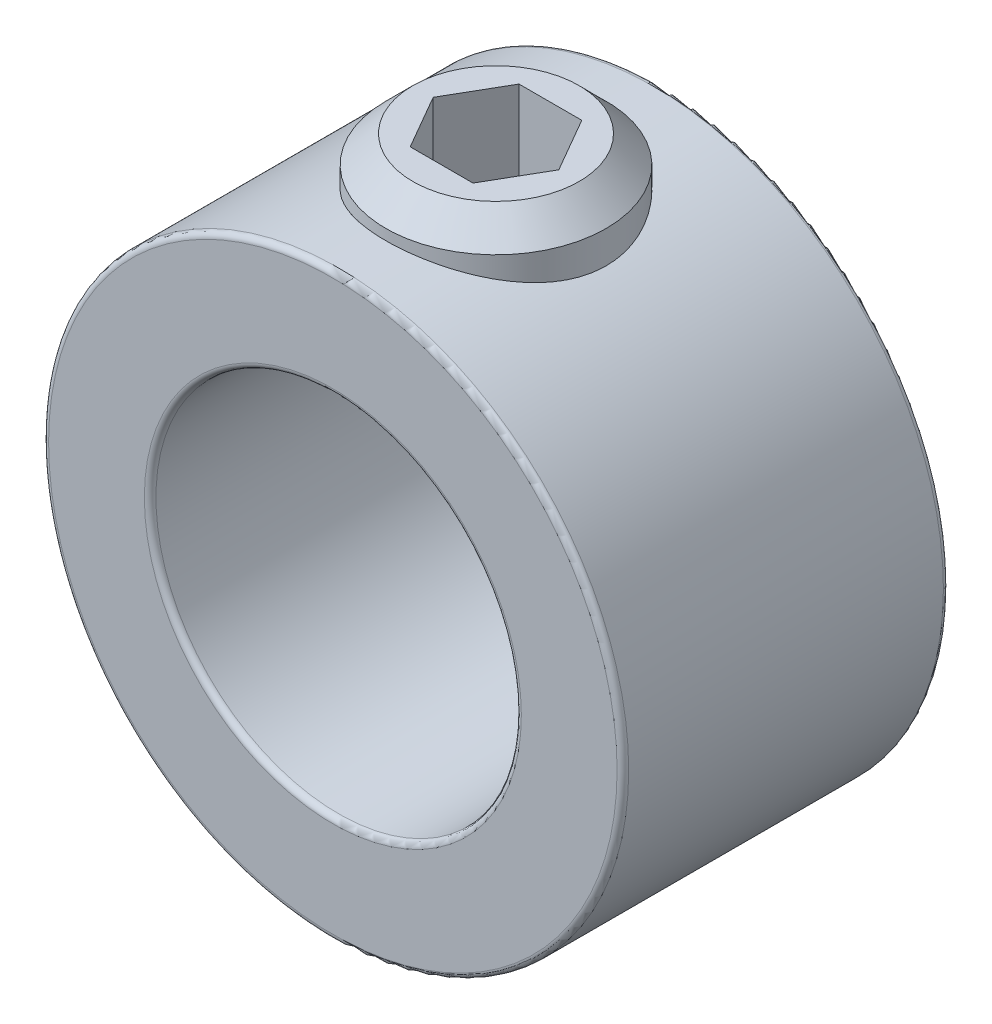
SolidWorks part; units mm, degrees
ref_plane "Front Plane" through (0, 0, 0) normal (0, 0, 1) x (1, 0, 0)
ref_plane "Top Plane" through (0, 0, 0) normal (0, 1, 0) x (1, 0, 0)
ref_plane "Right Plane" through (0, 0, 0) normal (1, 0, 0) x (0, 0, -1)
sketch "Sketch1" plane through (0, 0, 0) normal (0, 0, 1) x (1, 0, 0)
  circle A0 centre (0, 0) radius 6.35
  circle A1 centre (0, 0) radius 4
  point P4 (6.35, 0)
  dimension "Bore Dia" = 8
  dimension "OD" = 12.7
extrude "Extrude1" add sketch "Sketch1" along normal mid plane 7.1437
sketch "Sketch2" plane through (41.275, 0, 0) normal (0, -1, 0) x (0, 0, -1)
  line L0 (3.5719, -41.275) -> (-3.5719, -41.275) construction
  line L1 (-3.5719, -34.925) -> (-3.5719, -47.625) construction
  line L2 (3.5719, -47.625) -> (3.5719, -34.925) construction
  circle A0 centre (0, -41.275) radius 2.413
  point P7 (0, -43.688)
  dimension "Set Screw Dia" = 4.826
extrude "Cut-Extrude1" cut sketch "Sketch2" against normal through all
fillet "Fillet1" radius 0.127 4 edges at (4, 0, -3.5719) (4, 0, 3.5719) (6.35, 0, -3.5719) (6.35, 0, 3.5719)
sketch "Sketch3" plane through (0, 0, 0) normal (0, 0, 1) x (1, 0, 0)
  line L0 (-1.8198, 4) -> (-0.7119, 4)
  line L1 (0, 4.7119) -> (-0.7119, 4)
  line L2 (0, 4.7119) -> (0, 7.175)
  line L3 (0, 7.175) -> (-1.8198, 7.175)
  line L4 (-2.413, 4.5932) -> (-2.413, 6.5818)
  line L5 (0, 4) -> (0, 0) construction
  line L6 (-2.413, 4.5932) -> (-2.413, 4) construction
  line L7 (-2.413, 4) -> (-1.8198, 4) construction
  line L8 (-2.413, 6.5818) -> (-2.413, 7.175) construction
  line L9 (-1.8198, 4) -> (-2.413, 4.5932)
  line L10 (-2.413, 6.5818) -> (-1.8198, 7.175)
  line L11 (-2.413, 7.175) -> (-1.8198, 7.175) construction
  line L12 (-0.7119, 4) -> (0, 4) construction
  line L13 (0, 4) -> (0, 4.7119) construction
  circle A1 centre (0, 0) radius 4 construction
  dimension "Screw Length" = 3.175
  dimension "D2" = 0.5932
  dimension "D1" = 0.7119
revolve "Revolve1" add sketch "Sketch3" angle 360 about L5
sketch "Sketch4" plane through (3.3734, 7.175, 0) normal (0, -1, 0) x (0, 0, -1)
  line L1 (0, -1.9986) -> (-1.1906, -2.686)
  line L2 (-1.1906, -2.686) -> (-1.1906, -4.0608)
  line L3 (-1.1906, -4.0608) -> (0, -4.7483)
  line L4 (0, -4.7483) -> (1.1906, -4.0608)
  line L5 (1.1906, -4.0608) -> (1.1906, -2.686)
  line L6 (1.1906, -2.686) -> (0, -1.9986)
  circle A0 centre (0, -3.3734) radius 1.1906 construction
  circle A1 centre (0, -3.3734) radius 1.3748 construction
  dimension "Hex Size" = 2.3813
extrude "Cut-Extrude2" cut sketch "Sketch4" along normal blind 2.3813
equation "\"D1@Fillet1\" = \"OD@Sketch1\"*.01"
equation "\"D1@Cut-Extrude2\" = \"Hex Size@Sketch4\""
equation "\"D2@Sketch3\" =(\"Set Screw Dia@Sketch2\"-\"D1@Sketch4\")/3.5"
equation "\"D1@Sketch3\" = \"D2@Sketch3\"*1.2"
